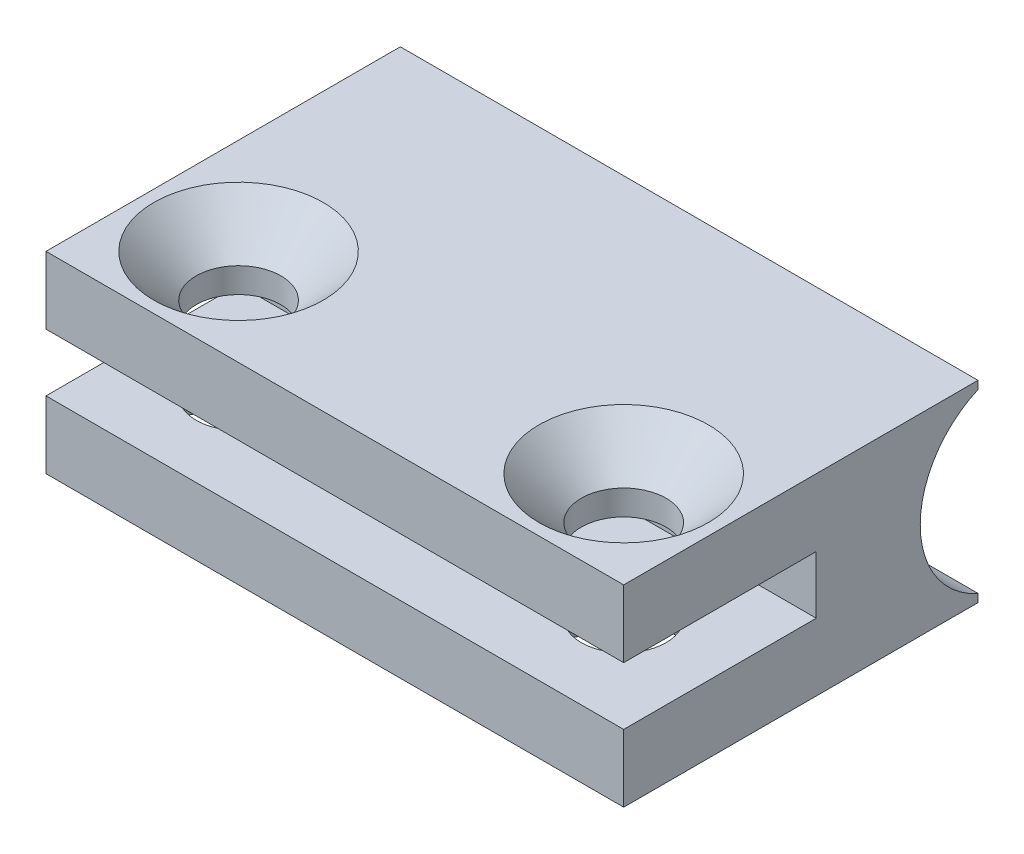
SolidWorks part; units mm, degrees
material "ПК/АБС"
ref_plane "Спереди" through (0, 0, 0) normal (0, 0, 1) x (1, 0, 0)
ref_plane "Сверху" through (0, 0, 0) normal (0, 1, 0) x (1, 0, 0)
ref_plane "Справа" through (0, 0, 0) normal (1, 0, 0) x (0, 0, -1)
sketch "Эскиз1" plane through (0, 0, 0) normal (1, 0, 0) x (0, 0, -1)
  line L0 (0, 2.5) -> (0, 0.75)
  line L1 (0, 0.75) -> (5, 0.75)
  line L2 (5, 0.75) -> (5, -0.75)
  line L3 (5, -0.75) -> (0, -0.75)
  line L4 (0, -0.75) -> (0, -2.5)
  line L5 (0, -2.5) -> (10.2, -2.5)
  line L6 (0, 2.5) -> (10.2, 2.5)
  line L7 (10.2, 3.4493) -> (10.2, -3.5457) construction
  arc A0 (10.2, 2.5) -> (10.2, -2.5) centre (10.2, 0) ccw
  point P2 (7.7, 0)
  dimension "D1" = 5
  dimension "D2" = 1.5
  dimension "D3" = 0.75
  dimension "D4" = 5
  dimension "D5" = 1.75
  dimension "D6" = 1.75
  dimension "D7" = 2.7
extrude "Бобышка-Вытянуть1" add sketch "Эскиз1" along normal blind 15 contours A0 L6 L0 L1 L2 L3 L4 L5
sketch "Эскиз2" plane through (15, 0, 0) normal (1, 0, 0) x (0, 0, -1)
  line L0 (10.2, 2.5) -> (10.2, -2.5) construction
  line L1 (0, 0) -> (11.8376, 0) construction
  line L3 (10.2, 2.5) -> (9.2, 2.5)
  line L4 (10.2, 2.5) -> (10.2, 1.5)
  line L5 (10.2, 1.5) -> (9.2, 1.5)
  line L6 (9.2, 2.5) -> (9.2, 1.5)
  line L7 (10.2, -2.5) -> (10.2, -1.5)
  line L8 (10.2, -1.5) -> (9.2, -1.5)
  line L9 (9.2, -2.5) -> (9.2, -1.5)
  line L10 (10.2, -2.5) -> (9.2, -2.5)
  arc A0 (10.2, 2.5) -> (10.2, -2.5) centre (10.2, 0) ccw construction
  dimension "D1" = 1
  dimension "D2" = 1
extrude "Вырез-Вытянуть1" cut sketch "Эскиз2" against normal blind 15
hole_wizard "Зенковка для винта с полупотайной головкой M21" positions "Эскиз4" profile "Эскиз3" countersink size "M2" standard "ISO" end condition through all
sketch "Эскиз4" plane through (0, 2.5, 0) normal (0, 1, 0) x (1, 0, 0)
  line L0 (15, 0) -> (0, 0) construction
  line L1 (15, 0) -> (15, 9.2) construction
  line L2 (0, 0) -> (0, 9.2) construction
  point P0 (12.5, 2.5)
  point P2 (2.5, 2.5)
  dimension "D1" = 2.5
  dimension "D2" = 2.5
  dimension "D3" = 2.5
  dimension "D4" = 2.5
sketch "Эскиз3" plane through (12.5, 2.5, -2.5) normal (1, 0, 0) x (0, 0, 1)
  line L0 (0, 0) -> (0, 5)
  line L1 (0, 5) -> (1.1, 5)
  line L2 (1.1, 5) -> (1.1, 1.1)
  line L3 (1.1, 1.1) -> (2.2, 0)
  line L5 (2.2, 0) -> (0, 0)
  line L6 (-1.1, 1.1) -> (-2.2, 0) construction
  line L11 (0, -6.35) -> (0, 107.95) construction
  dimension "Диаметр сквозного отверстия" = 2.2
  dimension "Глубина сквозного отверстия" = 5
  dimension "Диаметр передней зенковки" = 4.4
  dimension "Угол передней зенковки" = 90
sketch "Эскиз5" plane through (0, -2.5, 0) normal (0, -1, 0) x (1, 0, 0)
  line L0 (15, 0) -> (0, 0) construction
  line L2 (1.3211, -0.4581) -> (0.1423, -2.5)
  line L3 (0.1423, -2.5) -> (1.3211, -4.5419)
  line L4 (1.3211, -4.5419) -> (3.6789, -4.5419)
  line L5 (3.6789, -4.5419) -> (4.8577, -2.5)
  line L6 (4.8577, -2.5) -> (3.6789, -0.4581)
  line L7 (7.5, 0) -> (7.5, -5) construction
  line L8 (15, -5) -> (0, -5) construction
  line L9 (13.6789, -4.5419) -> (11.3211, -4.5419)
  line L10 (11.3211, -4.5419) -> (10.1423, -2.5)
  line L11 (14.8577, -2.5) -> (13.6789, -4.5419)
  line L12 (13.6789, -0.4581) -> (14.8577, -2.5)
  line L15 (3.6789, -0.4581) -> (1.3211, -0.4581)
  line L16 (0, 0) -> (0, -9.2) construction
  line L17 (2.4986, -0.5081) -> (1.4118, -0.5081) construction
  line L18 (11.3211, -0.4581) -> (13.6789, -0.4581)
  line L19 (10.1423, -2.5) -> (11.3211, -0.4581)
  circle A0 centre (2.5, -2.5) radius 2.0419 construction
  dimension "D1" = 2.5
  dimension "D2" = 2.5
  dimension "D5" = 0.05
extrude "Вырез-Вытянуть2" cut sketch "Эскиз5" against normal blind 1.2
